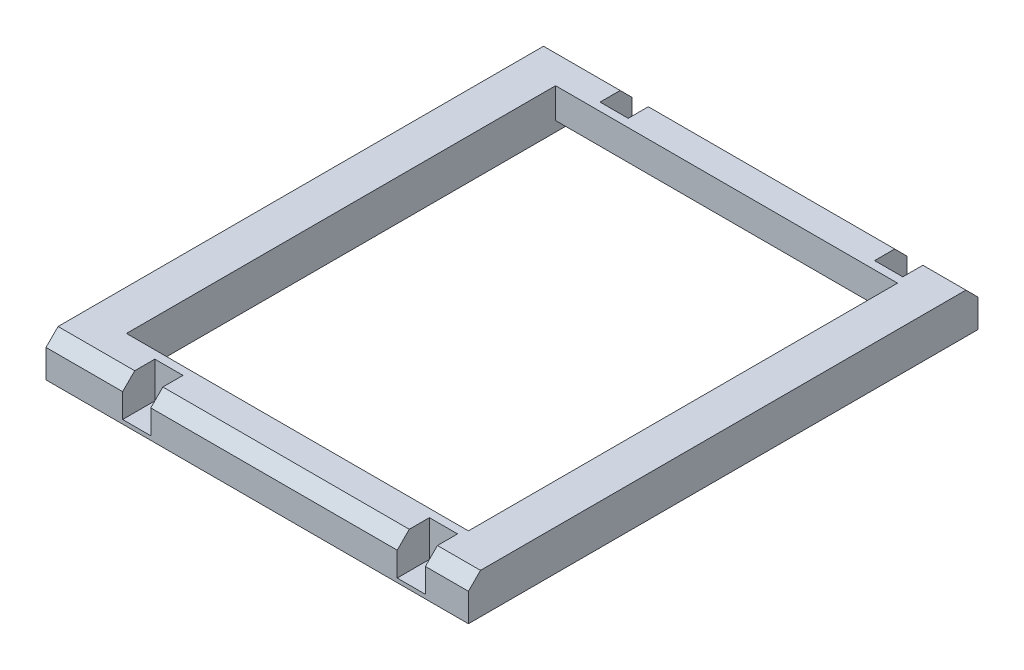
SolidWorks part; units mm, degrees
ref_plane "Front Plane" through (0, 0, 0) normal (0, 0, 1) x (1, 0, 0)
ref_plane "Top Plane" through (0, 0, 0) normal (0, 1, 0) x (1, 0, 0)
ref_plane "Right Plane" through (0, 0, 0) normal (1, 0, 0) x (0, 0, -1)
sketch "Sketch2" plane through (0, 0, 0) normal (0, 1, 0) x (1, 0, 0)
  line L1 (-66.675, -80.4333) -> (66.675, -80.4333)
  line L2 (-66.675, -80.4333) -> (-66.675, 80.4333)
  line L3 (-66.675, 80.4333) -> (66.675, 80.4333)
  line L4 (66.675, -80.4333) -> (66.675, 80.4333)
  line L5 (53.975, -67.7333) -> (-53.975, -67.7333)
  line L6 (53.975, -67.7333) -> (53.975, 67.7333)
  line L7 (53.975, 67.7333) -> (-53.975, 67.7333)
  line L8 (-53.975, -67.7333) -> (-53.975, 67.7333)
  point P4 (-66.675, 0)
  point P9 (0, -80.4333)
  point P11 (53.975, 0)
  point P12 (0, -67.7333)
  dimension "D1" = 12.7
  dimension "D2" = 12.7
  dimension "D3" = 160.8667
  dimension "D4" = 133.35
extrude "Boss-Extrude1" add sketch "Sketch2" along normal blind 12.7
sketch "Sketch4" plane through (0, 0, 0) normal (0, 1, 0) x (1, 0, 0)
  line L0 (-63.5, 76.2) -> (-60.325, 79.375)
  line L1 (-63.5, 76.2) -> (-60.325, 73.025)
  line L2 (-60.325, 79.375) -> (-57.15, 76.2)
  line L3 (-60.325, 73.025) -> (-57.15, 76.2)
  line L4 (-63.5, 76.2) -> (-57.15, 76.2) construction
  line L5 (-60.325, 79.375) -> (-60.325, 73.025) construction
  line L6 (-52.9167, 76.2) -> (-49.7417, 79.375)
  line L7 (-52.9167, 76.2) -> (-49.7417, 73.025)
  line L8 (-49.7417, 79.375) -> (-46.5667, 76.2)
  line L9 (-49.7417, 73.025) -> (-46.5667, 76.2)
  line L10 (-52.9167, 76.2) -> (-46.5667, 76.2) construction
  line L11 (-49.7417, 79.375) -> (-49.7417, 73.025) construction
  line L12 (57.15, 76.2) -> (60.325, 79.375)
  line L13 (57.15, 76.2) -> (60.325, 73.025)
  line L14 (60.325, 79.375) -> (63.5, 76.2)
  line L15 (60.325, 73.025) -> (63.5, 76.2)
  line L16 (57.15, 76.2) -> (63.5, 76.2) construction
  line L17 (60.325, 79.375) -> (60.325, 73.025) construction
  line L18 (57.15, -76.2) -> (60.325, -73.025)
  line L19 (57.15, -76.2) -> (60.325, -79.375)
  line L20 (60.325, -73.025) -> (63.5, -76.2)
  line L21 (60.325, -79.375) -> (63.5, -76.2)
  line L22 (57.15, -76.2) -> (63.5, -76.2) construction
  line L23 (60.325, -73.025) -> (60.325, -79.375) construction
  line L24 (-52.9167, -76.2) -> (-49.7417, -73.025)
  line L25 (-52.9167, -76.2) -> (-49.7417, -79.375)
  line L26 (-49.7417, -73.025) -> (-46.5667, -76.2)
  line L27 (-49.7417, -79.375) -> (-46.5667, -76.2)
  line L28 (-52.9167, -76.2) -> (-46.5667, -76.2) construction
  line L29 (-49.7417, -73.025) -> (-49.7417, -79.375) construction
  line L30 (-63.5, -76.2) -> (-60.325, -73.025)
  line L31 (-63.5, -76.2) -> (-60.325, -79.375)
  line L32 (-60.325, -73.025) -> (-57.15, -76.2)
  line L33 (-60.325, -79.375) -> (-57.15, -76.2)
  line L34 (-63.5, -76.2) -> (-57.15, -76.2) construction
  line L35 (-60.325, -73.025) -> (-60.325, -79.375) construction
  line L36 (-66.675, 80.4333) -> (-66.675, -80.4333) construction
  line L37 (66.675, 80.4333) -> (-66.675, 80.4333) construction
  line L38 (66.675, -80.4333) -> (66.675, 80.4333) construction
  line L39 (-66.675, -80.4333) -> (66.675, -80.4333) construction
  point P1 (-60.325, 76.2)
  point P2 (-49.7417, 76.2)
  point P3 (60.325, 76.2)
  point P8 (60.325, -76.2)
  point P13 (-49.7417, -76.2)
  point P18 (-60.325, -76.2)
  dimension "D1" = 6.35
  dimension "D2" = 4.2333
  dimension "D3" = 6.35
  dimension "D4" = 10.5833
  dimension "D5" = 6.35
  dimension "D6" = 4.2333
extrude "Cut-Extrude1" cut sketch "Sketch4" along normal blind 6.35
chamfer "Chamfer1" distance 0.635 angle 45 50 edges at (-61.9125, 6.35, -77.7875) (-58.7375, 6.35, -77.7875) (-58.7375, 6.35, -74.6125) (-61.9125, 6.35, -74.6125) (-51.3292, 6.35, -77.7875) (-48.1542, 6.35, -77.7875) (-48.1542, 6.35, -74.6125) (-51.3292, 6.35, -74.6125) (58.7375, 6.35, -77.7875) (61.9125, 6.35, -77.7875) (61.9125, 6.35, -74.6125) (58.7375, 6.35, -74.6125) (58.7375, 6.35, 74.6125) (61.9125, 6.35, 74.6125) (61.9125, 6.35, 77.7875) (58.7375, 6.35, 77.7875) (-51.3292, 6.35, 74.6125) (-48.1542, 6.35, 74.6125) (-48.1542, 6.35, 77.7875) (-51.3292, 6.35, 77.7875) (-61.9125, 6.35, 74.6125) (-58.7375, 6.35, 74.6125) (-58.7375, 6.35, 77.7875) (-61.9125, 6.35, 77.7875) (-61.9125, 0, -77.7875) (-61.9125, 0, -74.6125) (-58.7375, 0, -74.6125) (-58.7375, 0, -77.7875) (-51.3292, 0, -77.7875) (-48.1542, 0, -77.7875) (-48.1542, 0, -74.6125) (-51.3292, 0, -74.6125) (58.7375, 0, -77.7875) (61.9125, 0, -77.7875) (61.9125, 0, -74.6125) (58.7375, 0, -74.6125) (61.9125, 0, 74.6125) (61.9125, 0, 77.7875) (58.7375, 0, 77.7875) (58.7375, 0, 74.6125) (-52.9167, 3.175, 76.2) (-49.7417, 3.175, 73.025) (-51.3292, 0, 74.6125) (-48.1542, 0, 74.6125) (-48.1542, 0, 77.7875) (-51.3292, 0, 77.7875) (-61.9125, 0, 74.6125) (-58.7375, 0, 74.6125) (-58.7375, 0, 77.7875) (-61.9125, 0, 77.7875)
chamfer "Chamfer3" distance 3.81 angle 45 2 edges at (0, 12.7, 80.4333) (0, 12.7, -80.4333)
sketch "Sketch5" plane through (0, 0, 80.4333) normal (0, 0, 1) x (1, 0, 0)
  line L0 (-66.675, 12.7) -> (66.675, 12.7) construction
  line L1 (-42.4815, 1.27) -> (-33.5915, 1.27)
  line L2 (-42.4815, 1.27) -> (-42.4815, 12.7)
  line L3 (-42.4815, 12.7) -> (-33.5915, 12.7)
  line L4 (-33.5915, 1.27) -> (-33.5915, 12.7)
  line L5 (-66.675, 8.89) -> (-66.675, 0) construction
  line L6 (44.196, 1.27) -> (53.086, 1.27)
  line L7 (44.196, 1.27) -> (44.196, 12.7)
  line L8 (44.196, 12.7) -> (53.086, 12.7)
  line L9 (53.086, 1.27) -> (53.086, 12.7)
  point P10 (44.1942, 1.3225)
  point P11 (53.0585, 1.2516)
  dimension "D1" = 8.89
  dimension "D2" = 8.89
  dimension "D3" = 24.1935
  dimension "D4" = 77.7875
  dimension "D5" = 11.43
extrude "Cut-Extrude2" cut sketch "Sketch5" against normal offset from surface (10.16 mm away) 2.54 up to face at (0, 6.35, 67.7333)
sketch "Sketch6" plane through (0, 0, -80.4333) normal (0, 0, -1) x (-1, 0, 0)
  line L1 (42.4815, 1.27) -> (33.5915, 1.27)
  line L2 (42.4815, 1.27) -> (42.4815, 12.7)
  line L3 (42.4815, 12.7) -> (33.5915, 12.7)
  line L4 (33.5915, 1.27) -> (33.5915, 12.7)
  line L5 (-44.196, 1.27) -> (-53.086, 1.27)
  line L6 (-44.196, 1.27) -> (-44.196, 12.7)
  line L7 (-44.196, 12.7) -> (-53.086, 12.7)
  line L8 (-53.086, 1.27) -> (-53.086, 12.7)
extrude "Cut-Extrude3" cut sketch "Sketch6" against normal offset from surface (10.16 mm away) 2.54 up to face at (0, 6.35, -67.7333)
chamfer "Chamfer4" distance 3.175 angle 45 2 edges at (0, 0, 67.7333) (0, 0, -67.7333)
